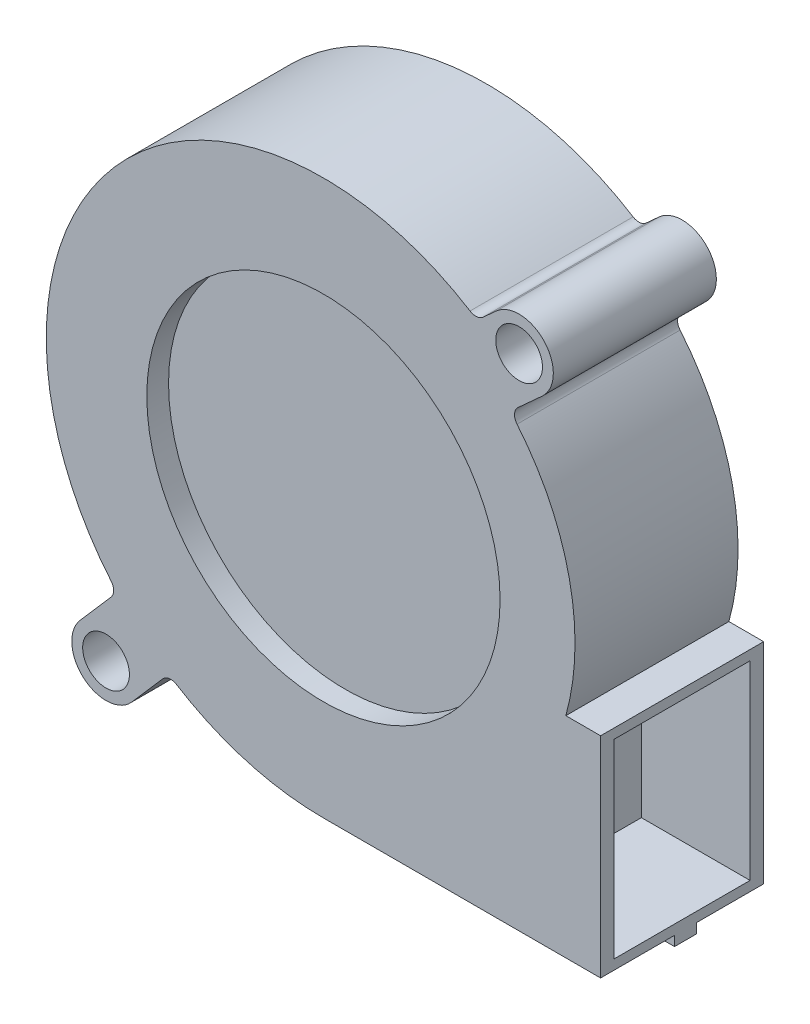
SolidWorks part; units mm, degrees
ref_plane "Front" through (0, 0, 0) normal (0, 0, 1) x (1, 0, 0)
ref_plane "Top" through (0, 0, 0) normal (0, 1, 0) x (1, 0, 0)
ref_plane "Right" through (0, 0, 0) normal (1, 0, 0) x (0, 0, -1)
sketch "Sketch1" plane through (0, 0, 0) normal (0, 0, 1) x (1, 0, 0)
  line L0 (0, 0) -> (-25.5, 0) construction
  line L1 (25.5, -25.5) -> (0, -25.5)
  line L2 (25.5, -25.5) -> (25.5, -6.2)
  line L3 (25.5, -6.2) -> (0, -6.2)
  line L4 (0, -25.5) -> (0, -6.2)
  line L5 (25.5, -25.5) -> (0, -6.2) construction
  line L6 (25.5, -6.2) -> (0, -25.5) construction
  line L7 (-17.623, -25.067) -> (-14.7972, -21.8173)
  line L8 (-14.2274, -21.162) -> (-18.9814, -17.0281) construction
  line L9 (-22.377, -20.933) -> (-19.5512, -17.6834)
  line L10 (15.8812, 22.8309) -> (14.6907, 21.7488)
  line L11 (14.1225, 21.2322) -> (18.9284, 17.087) construction
  line L12 (18.9284, 17.087) -> (20.1188, 18.1691)
  line L13 (18.9284, 17.087) -> (17.9083, 16.1597)
  arc A0 (-13.5127, -21.6254) -> (24.7348, -6.2) centre (0, 0) ccw
  circle A1 centre (18, 20.5) radius 2.15
  circle A2 centre (-20, -23) radius 2.15
  circle A3 centre (18, 20.5) radius 3.15
  circle A4 centre (-20, -23) radius 3.15
  arc A5 (-18.9814, -17.0281) -> (-14.2274, -21.162) centre (0, 0) ccw construction
  arc A6 (-14.7972, -21.8173) -> (-13.5127, -21.6254) centre (-14.0426, -22.4735) cw
  arc A7 (-19.5395, -16.3846) -> (-19.5512, -17.6834) centre (-20.3058, -17.0272) cw
  arc A8 (13.4891, 21.6401) -> (-19.5395, -16.3846) centre (0, 0) ccw
  arc A9 (14.858, 20.7241) -> (14.1225, 21.2322) centre (0, 0) ccw construction
  arc A10 (18.6286, 17.4134) -> (14.858, 20.7241) centre (0, 0) ccw construction
  arc A11 (18.9284, 17.087) -> (18.6286, 17.4134) centre (0, 0) ccw construction
  arc A12 (17.1864, 15.5035) -> (-23.1458, 0) centre (0, 0) ccw construction
  arc A13 (22.3, -6.2) -> (17.8115, 14.7811) centre (0, 0) ccw
  arc A14 (-23.1458, 0) -> (21.089, -9.5385) centre (0, 0) ccw construction
  arc A15 (21.089, -9.5385) -> (22.3, -6.2) centre (0, 0) ccw construction
  arc A16 (24.7348, -6.2) -> (18.9284, 17.087) centre (0, 0) ccw construction
  arc A17 (17.8115, 14.7811) -> (17.9083, 16.1597) centre (18.581, 15.4198) cw
  arc A18 (14.6907, 21.7488) -> (13.4891, 21.6401) centre (14.0181, 22.4887) cw
  point P7 (12.75, -15.85)
  point P29 (22.3, -6.2)
  dimension "D1" = 51
  dimension "D6" = 4.3
  dimension "D9" = 1
  dimension "D10" = 1
  dimension "D11" = 1
  dimension "D2" = 51
  dimension "D3" = 19.3
  dimension "D4" = 18
  dimension "D5" = 20.5
  dimension "D7" = 23
  dimension "D8" = 20
  dimension "D12" = 3.2
extrude "Boss-Extrude1" add sketch "Sketch1" along normal mid plane 15
sketch "Sketch3" plane through (25.5, 0, 0) normal (1, 0, 0) x (0, 0, -1)
  line L0 (-7.5, -25.5) -> (7.5, -25.5) construction
  line L1 (-0.7, -25.5) -> (1.3, -25.5)
  line L2 (-0.7, -25.5) -> (-0.7, -26.4)
  line L3 (-0.7, -26.4) -> (1.3, -26.4)
  line L4 (1.3, -25.5) -> (1.3, -26.4)
  line L5 (-0.7, -25.5) -> (1.3, -26.4) construction
  line L6 (-0.7, -26.4) -> (1.3, -25.5) construction
  point P4 (0.3, -25.95)
  point P7 (0, 0)
  point P9 (-0.7899, -25.95)
  dimension "D1" = 0.9
  dimension "D2" = 8.2
  dimension "D3" = 8.8
extrude "Boss-Extrude2" add sketch "Sketch3" against normal blind 11.4
sketch "Sketch4" plane through (0, 0, 7.5) normal (0, 0, 1) x (1, 0, 0)
  circle A0 centre (0, 0) radius 16.25
  dimension "D1" = 32.5
extrude "Cut-Extrude1" cut sketch "Sketch4" against normal blind 2
sketch "Sketch5" plane through (25.5, 0, 0) normal (1, 0, 0) x (0, 0, -1)
  line L0 (-7.5, -25.5) -> (-7.5, -6.2) construction
  line L1 (-6.25, -7.1) -> (6.25, -7.1)
  line L2 (-6.25, -7.1) -> (-6.25, -24.6)
  line L3 (-6.25, -24.6) -> (6.25, -24.6)
  line L4 (6.25, -7.1) -> (6.25, -24.6)
  line L5 (-6.25, -7.1) -> (6.25, -24.6) construction
  line L6 (-6.25, -24.6) -> (6.25, -7.1) construction
  point P4 (0, -15.85)
  point P9 (-7.5, -15.85)
  dimension "D1" = 12.5
  dimension "D2" = 17.5
extrude "Cut-Extrude2" cut sketch "Sketch5" against normal blind 10
